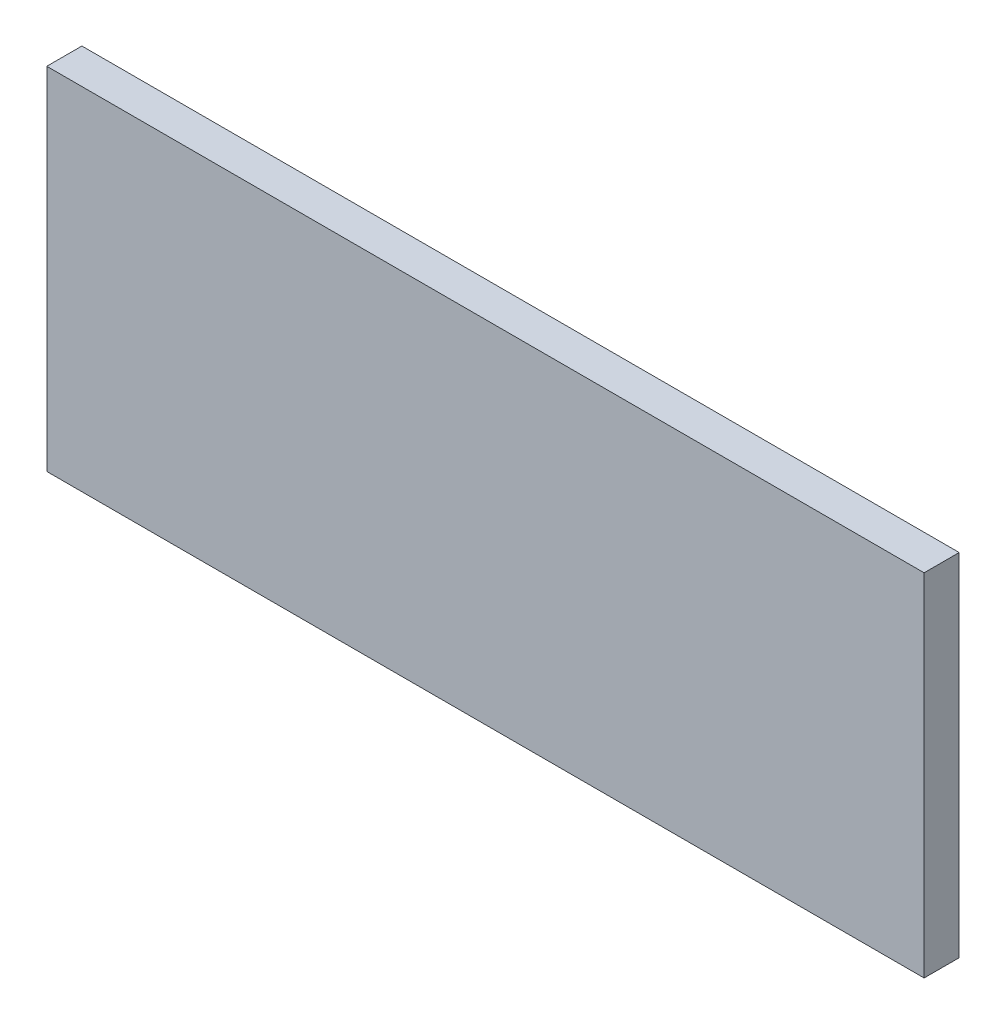
SolidWorks part; units mm, degrees
material "轻木"
ref_plane "前视基准面" through (0, 0, 0) normal (0, 0, 1) x (1, 0, 0)
ref_plane "上视基准面" through (0, 0, 0) normal (0, 1, 0) x (1, 0, 0)
ref_plane "右视基准面" through (0, 0, 0) normal (1, 0, 0) x (0, 0, -1)
sketch "草图1" plane through (0, 0, 0) normal (0, 0, 1) x (1, 0, 0)
  line L1 (-25, 10) -> (25, 10)
  line L2 (-25, 10) -> (-25, -10)
  line L3 (-25, -10) -> (25, -10)
  line L4 (25, 10) -> (25, -10)
  line L5 (-25, 10) -> (25, -10) construction
  line L6 (-25, -10) -> (25, 10) construction
  point P0 (0, 0)
  dimension "D1" = 50
  dimension "D2" = 20
extrude "凸台-拉伸1" add sketch "草图1" along normal blind 2
